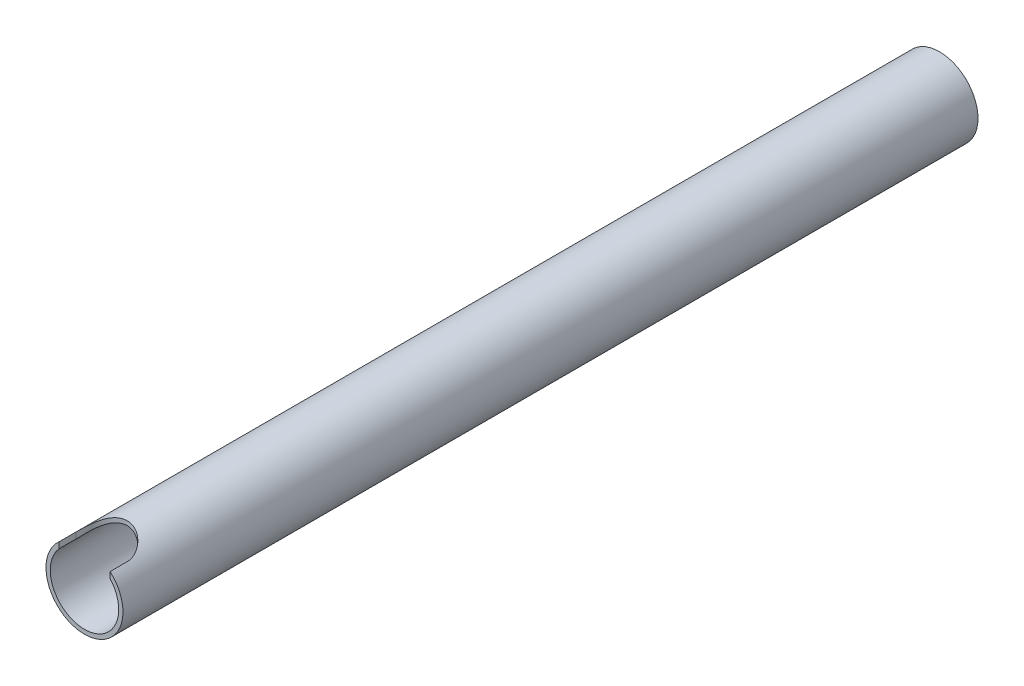
SolidWorks part; units mm, degrees
material "cf"
ref_plane "Front Plane" through (0, 0, 0) normal (0, 0, 1) x (1, 0, 0)
ref_plane "Top Plane" through (0, 0, 0) normal (0, 1, 0) x (1, 0, 0)
ref_plane "Right Plane" through (0, 0, 0) normal (1, 0, 0) x (0, 0, -1)
sketch "Sketch1" plane through (0, 0, 0) normal (0, 0, 1) x (1, 0, 0)
  circle A0 centre (0, 0) radius 8
  circle A1 centre (0, 0) radius 9
  dimension "D1" = 18
  dimension "D2" = 16
extrude "Boss-Extrude1" add sketch "Sketch1" along normal blind 200
ref_plane "Plane1" through (0, 10, 0) normal (0, 1, 0) x (1, 0, 0)
sketch "Sketch2" plane through (0, 10, 0) normal (0, 1, 0) x (1, 0, 0)
  line L0 (0, -204) -> (0, -196) construction
  line L1 (-9, -200) -> (9, -200) construction
  line L2 (-6, -204) -> (-6, -196)
  line L3 (6, -204) -> (6, -196)
  arc A0 (-6, -204) -> (6, -204) centre (0, -204) ccw
  arc A1 (6, -196) -> (-6, -196) centre (0, -196) ccw
  point P5 (0, -200)
  dimension "D2" = 6
  dimension "D1" = 4
extrude "Cut-Extrude1" cut sketch "Sketch2" against normal blind 10
